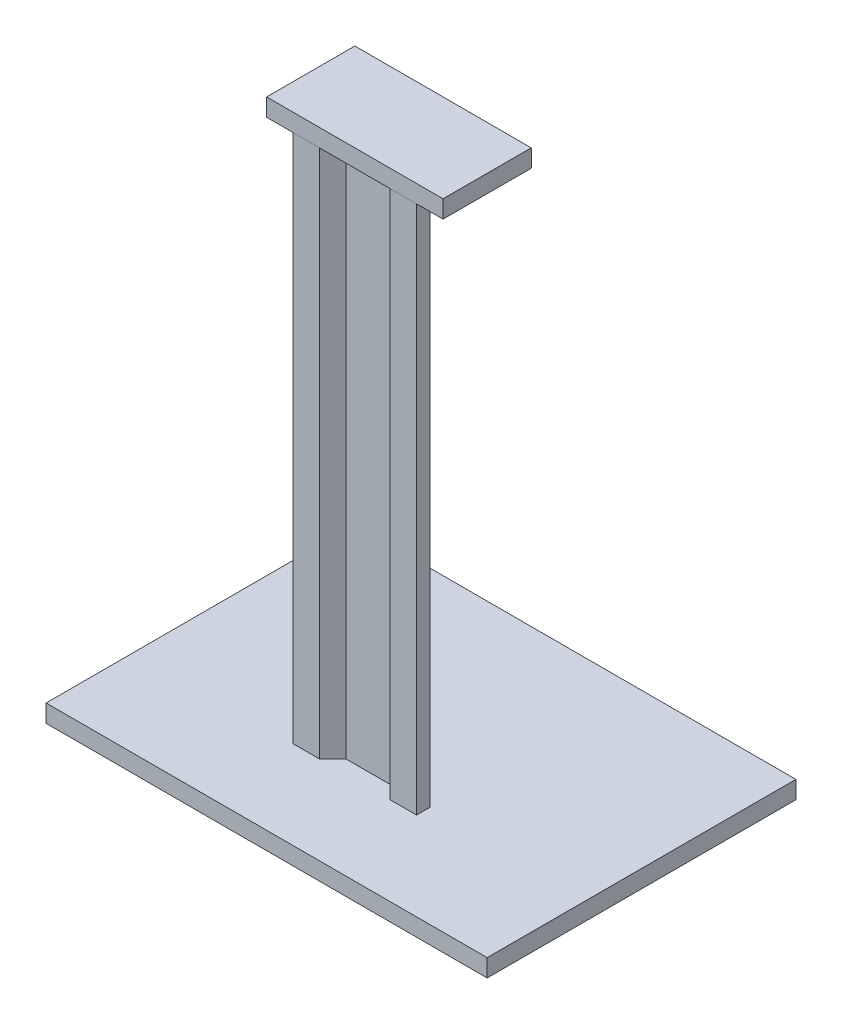
SolidWorks part; units mm, degrees
material "Aleación 1060"
ref_plane "Alzado" through (0, 0, 0) normal (0, 0, 1) x (1, 0, 0)
ref_plane "Planta" through (0, 0, 0) normal (0, 1, 0) x (1, 0, 0)
ref_plane "Vista lateral" through (0, 0, 0) normal (1, 0, 0) x (0, 0, -1)
sketch "Croquis1" plane through (0, 0, 0) normal (0, 1, 0) x (1, 0, 0)
  line L0 (0, 0) -> (0, 116.3193) construction
  line L1 (25, 15) -> (-25, 15)
  line L2 (-25, 15) -> (-40, 0)
  line L3 (-40, 0) -> (-70, 0)
  line L4 (-70, 0) -> (-70, 15)
  line L5 (-70, 15) -> (-46.2132, 15)
  line L6 (-46.2132, 15) -> (-10.6066, 50.6066)
  line L7 (-10.6066, 50.6066) -> (0, 40)
  line L8 (0, 0) -> (-40, 0) construction
  line L9 (70, 15) -> (46.2132, 15)
  line L10 (25, 15) -> (40, 0)
  line L11 (40, 0) -> (70, 0)
  line L12 (70, 0) -> (70, 15)
  line L13 (46.2132, 15) -> (10.6066, 50.6066)
  line L14 (10.6066, 50.6066) -> (0, 40)
  circle A0 centre (0, 61.2132) radius 15 construction
  point P5 (-10.0111, 50.0428)
  point P17 (0, 15)
  dimension "D8" = 30
  dimension "D1" = 15
  dimension "D2" = 70
  dimension "D3" = 45
  dimension "D4" = 25
  dimension "D5" = 45
  dimension "D6" = 40
extrude "Saliente-Extruir1" add sketch "Croquis1" along normal blind 600
sketch "Croquis2" plane through (0, 0, 0) normal (0, -1, 0) x (1, 0, 0)
  line L0 (0, 0) -> (0, 27.9383) construction
  line L2 (-250, -250) -> (250, -250)
  line L3 (-250, -250) -> (-250, 100)
  line L4 (-250, 100) -> (250, 100)
  line L5 (250, -250) -> (250, 100)
  point P0 (0, 0)
  point P8 (0, 0)
  point P9 (0, 0)
  dimension "D1" = 250
  dimension "D2" = 100
  dimension "D3" = 500
  dimension "D4" = 250
extrude "Saliente-Extruir2" add sketch "Croquis2" along normal blind 20
sketch "Croquis3" plane through (0, 0, -15) normal (0, 0, -1) x (-1, 0, 0)
  line L0 (58.1066, 600) -> (58.1066, 0) construction
  line L1 (46.2132, 600) -> (70, 600) construction
  line L2 (46.2132, 0) -> (70, 0) construction
  line L4 (56.6066, 0) -> (59.6066, 0)
  line L5 (56.6066, 0) -> (56.6066, 600)
  line L6 (56.6066, 600) -> (59.6066, 600)
  line L7 (59.6066, 0) -> (59.6066, 600)
  line L8 (56.6066, 0) -> (59.6066, 600) construction
  line L9 (56.6066, 600) -> (59.6066, 0) construction
  point P6 (58.1066, 300)
  dimension "D1" = 3
extrude "Cortar-Extruir1" cut sketch "Croquis3" against normal blind 2
mirror "Simetría1" about plane through (0, 0, 0) normal (1, 0, 0) of "Cortar-Extruir1"
sketch "Croquis4" plane through (0, 600, 0) normal (0, 1, 0) x (1, 0, 0)
  line L0 (10.6066, 50.6066) -> (0, 40) construction
  line L1 (0, 40) -> (-10.6066, 50.6066) construction
  circle A0 centre (0, 61.2132) radius 15
  dimension "D1" = 30
extrude "Saliente-Extruir3" add sketch "Croquis4" against normal up to next separate body
sketch "Croquis6" plane through (0, 600, 0) normal (0, 1, 0) x (1, 0, 0)
  line L0 (-70, 0) -> (-40, 0) construction
  line L1 (-100, 0) -> (100, 0)
  line L2 (-100, 0) -> (-100, 100)
  line L3 (-100, 100) -> (100, 100)
  line L4 (100, 0) -> (100, 100)
  dimension "D1" = 200
  dimension "D2" = 100
  dimension "D3" = 100
extrude "Saliente-Extruir5" add sketch "Croquis6" along normal blind 20 separate body
